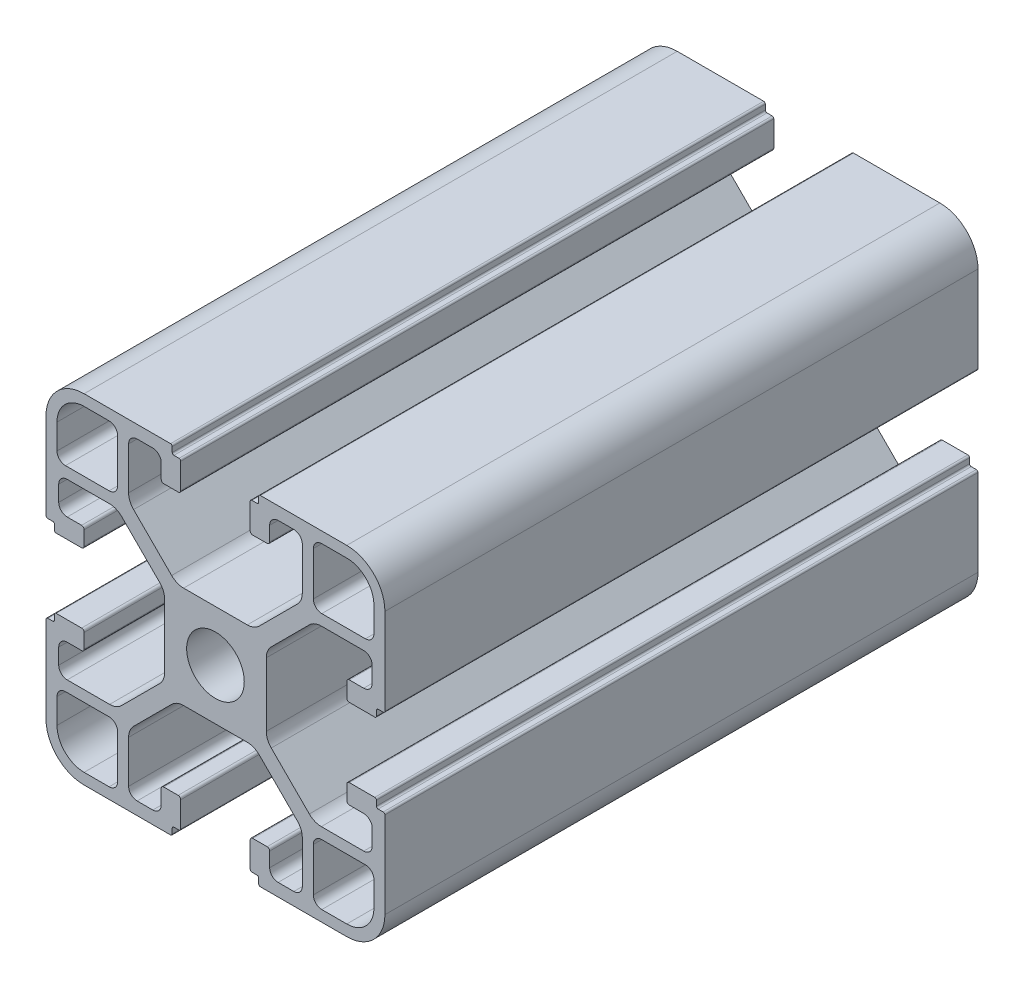
SolidWorks part; units mm, degrees
material "6063-T5"
ref_plane "Front Plane" through (0, 0, 0) normal (0, 0, 1) x (1, 0, 0)
ref_plane "Top Plane" through (0, 0, 0) normal (0, 1, 0) x (1, 0, 0)
ref_plane "Right Plane" through (0, 0, 0) normal (1, 0, 0) x (0, 0, -1)
sketch "Sketch2" plane through (0, 0, 0) normal (0, 0, 1) x (1, 0, 0)
  line L0 (4.5, 0) -> (14.7, 0)
  line L1 (40, 4.5) -> (40, 14.7)
  line L2 (35.5, 40) -> (25.3, 40)
  line L3 (0, 35.5) -> (0, 25.3)
  line L4 (15.9, 1.2) -> (15.9, 4.2)
  line L5 (24.1, 1.2) -> (24.1, 4.2)
  line L6 (38.8, 24.1) -> (35.8, 24.1)
  line L7 (35.5, 24.4) -> (35.5, 26.1)
  line L8 (14, 23.7574) -> (14, 16.2426)
  line L9 (16.2426, 14) -> (23.7574, 14)
  line L10 (26, 16.2426) -> (26, 23.7574)
  line L11 (13.4142, 14.8284) -> (8.9216, 10.3358)
  line L12 (23.7574, 26) -> (16.2426, 26)
  line L13 (4.5, 24.4) -> (4.5, 26.1)
  line L14 (1.2, 24.1) -> (4.2, 24.1)
  line L15 (15.9, 38.8) -> (15.9, 35.8)
  line L16 (14.8284, 26.5858) -> (10.3358, 31.0784)
  line L17 (13.4142, 25.1716) -> (8.9216, 29.6642)
  line L18 (14.8284, 13.4142) -> (10.3358, 8.9216)
  line L19 (25.1716, 13.4142) -> (29.6642, 8.9216)
  line L20 (26.5858, 14.8284) -> (31.0784, 10.3358)
  line L21 (26.5858, 25.1716) -> (31.0784, 29.6642)
  line L22 (25.1716, 26.5858) -> (29.6642, 31.0784)
  line L23 (24.1, 38.8) -> (24.1, 35.8)
  line L24 (14.7, 40) -> (4.5, 40)
  line L25 (25.3, 0) -> (35.5, 0)
  line L26 (38.8, 15.9) -> (35.8, 15.9)
  line L27 (40, 25.3) -> (40, 35.5)
  line L28 (1.2, 15.9) -> (4.2, 15.9)
  line L29 (0, 14.7) -> (0, 4.5)
  line L30 (4.5, 15.6) -> (4.5, 13.9)
  line L31 (35.5, 15.6) -> (35.5, 13.9)
  line L32 (15.6, 35.5) -> (13.9, 35.5)
  line L33 (24.4, 35.5) -> (26.1, 35.5)
  line L34 (15.6, 4.5) -> (13.9, 4.5)
  line L35 (24.4, 4.5) -> (26.1, 4.5)
  line L36 (12.6, 38.5) -> (10.75, 38.5)
  line L37 (1.5, 12.6) -> (1.5, 10.75)
  line L38 (27.4, 1.5) -> (29.25, 1.5)
  line L39 (38.5, 27.4) -> (38.5, 29.25)
  line L40 (38.5, 10.75) -> (38.5, 12.6)
  line L41 (29.25, 38.5) -> (27.4, 38.5)
  line L42 (1.5, 29.25) -> (1.5, 27.4)
  line L43 (10.75, 1.5) -> (12.6, 1.5)
  line L44 (35.8, 26.4) -> (37.5, 26.4)
  line L45 (35.8, 13.6) -> (37.5, 13.6)
  line L46 (4.2, 26.4) -> (2.5, 26.4)
  line L47 (13.6, 35.8) -> (13.6, 37.5)
  line L48 (26.4, 35.8) -> (26.4, 37.5)
  line L49 (4.2, 13.6) -> (2.5, 13.6)
  line L50 (13.6, 4.2) -> (13.6, 2.5)
  line L51 (26.4, 4.2) -> (26.4, 2.5)
  line L52 (9.75, 7.5074) -> (9.75, 2.5)
  line L53 (30.25, 7.5074) -> (30.25, 2.5)
  line L54 (9.75, 37.5) -> (9.75, 32.4926)
  line L55 (30.25, 37.5) -> (30.25, 32.4926)
  line L56 (32.4926, 30.25) -> (37.5, 30.25)
  line L57 (37.5, 9.75) -> (32.4926, 9.75)
  line L58 (2.5, 30.25) -> (7.5074, 30.25)
  line L59 (2.5, 9.75) -> (7.5074, 9.75)
  line L60 (31.55, 37.7) -> (31.55, 32.55)
  line L61 (32.55, 31.55) -> (37.7, 31.55)
  line L62 (1.3, 35.5) -> (1.3, 32.55)
  line L63 (4.5, 38.7) -> (7.45, 38.7)
  line L64 (32.55, 38.7) -> (35.5, 38.7)
  line L65 (38.7, 35.5) -> (38.7, 32.55)
  line L66 (8.45, 37.7) -> (8.45, 32.55)
  line L67 (2.3, 31.55) -> (7.45, 31.55)
  line L68 (1.3, 7.45) -> (1.3, 4.5)
  line L69 (2.3, 8.45) -> (7.45, 8.45)
  line L70 (8.45, 7.45) -> (8.45, 2.3)
  line L71 (4.5, 1.3) -> (7.45, 1.3)
  line L72 (31.55, 7.45) -> (31.55, 2.3)
  line L73 (32.55, 8.45) -> (37.7, 8.45)
  line L74 (38.7, 7.45) -> (38.7, 4.5)
  line L75 (32.55, 1.3) -> (35.5, 1.3)
  line L77 (14.9, 39.8) -> (14.9, 39.2)
  line L78 (15.1, 39) -> (15.7, 39)
  line L79 (25.1, 39.8) -> (25.1, 39.2)
  line L80 (24.9, 39) -> (24.3, 39)
  line L81 (25.1, 0.2) -> (25.1, 0.8)
  line L82 (24.9, 1) -> (24.3, 1)
  line L83 (14.9, 0.2) -> (14.9, 0.8)
  line L84 (15.1, 1) -> (15.7, 1)
  line L85 (0.2, 25.1) -> (0.8, 25.1)
  line L86 (1, 24.9) -> (1, 24.3)
  line L87 (0.2, 14.9) -> (0.8, 14.9)
  line L88 (1, 15.1) -> (1, 15.7)
  line L89 (39.8, 25.1) -> (39.2, 25.1)
  line L90 (39, 24.9) -> (39, 24.3)
  line L91 (39, 15.7) -> (39, 15.1)
  line L92 (39.2, 14.9) -> (39.8, 14.9)
  circle A0 centre (20, 20) radius 3.4
  arc A1 (1.3, 35.5) -> (4.5, 38.7) centre (4.5, 35.5) cw
  arc A2 (1.3, 4.5) -> (4.5, 1.3) centre (4.5, 4.5) ccw
  arc A3 (38.7, 4.5) -> (35.5, 1.3) centre (35.5, 4.5) cw
  arc A4 (35.5, 38.7) -> (38.7, 35.5) centre (35.5, 35.5) cw
  arc A5 (40, 35.5) -> (35.5, 40) centre (35.5, 35.5) ccw
  arc A6 (35.5, 0) -> (40, 4.5) centre (35.5, 4.5) ccw
  arc A7 (4.5, 0) -> (0, 4.5) centre (4.5, 4.5) cw
  arc A8 (4.5, 40) -> (0, 35.5) centre (4.5, 35.5) ccw
  arc A9 (13.4142, 14.8284) -> (14, 16.2426) centre (12, 16.2426) ccw
  arc A10 (7.5074, 9.75) -> (8.9216, 10.3358) centre (7.5074, 11.75) ccw
  arc A11 (9.75, 7.5074) -> (10.3358, 8.9216) centre (11.75, 7.5074) cw
  arc A12 (30.25, 7.5074) -> (29.6642, 8.9216) centre (28.25, 7.5074) ccw
  arc A13 (14.8284, 13.4142) -> (16.2426, 14) centre (16.2426, 12) cw
  arc A14 (25.1716, 13.4142) -> (23.7574, 14) centre (23.7574, 12) ccw
  arc A15 (32.4926, 9.75) -> (31.0784, 10.3358) centre (32.4926, 11.75) cw
  arc A16 (26.5858, 14.8284) -> (26, 16.2426) centre (28, 16.2426) cw
  arc A17 (32.4926, 30.25) -> (31.0784, 29.6642) centre (32.4926, 28.25) ccw
  arc A18 (26.5858, 25.1716) -> (26, 23.7574) centre (28, 23.7574) ccw
  arc A19 (13.4142, 25.1716) -> (14, 23.7574) centre (12, 23.7574) cw
  arc A20 (7.5074, 30.25) -> (8.9216, 29.6642) centre (7.5074, 28.25) cw
  arc A21 (9.75, 32.4926) -> (10.3358, 31.0784) centre (11.75, 32.4926) ccw
  arc A22 (30.25, 32.4926) -> (29.6642, 31.0784) centre (28.25, 32.4926) cw
  arc A23 (25.1716, 26.5858) -> (23.7574, 26) centre (23.7574, 28) cw
  arc A24 (14.8284, 26.5858) -> (16.2426, 26) centre (16.2426, 28) ccw
  arc A25 (37.7, 8.45) -> (38.7, 7.45) centre (37.7, 7.45) cw
  arc A26 (31.55, 2.3) -> (32.55, 1.3) centre (32.55, 2.3) ccw
  arc A27 (31.55, 7.45) -> (32.55, 8.45) centre (32.55, 7.45) cw
  arc A28 (8.45, 2.3) -> (7.45, 1.3) centre (7.45, 2.3) cw
  arc A29 (1.3, 7.45) -> (2.3, 8.45) centre (2.3, 7.45) cw
  arc A30 (7.45, 8.45) -> (8.45, 7.45) centre (7.45, 7.45) cw
  arc A31 (38.7, 32.55) -> (37.7, 31.55) centre (37.7, 32.55) cw
  arc A32 (31.55, 32.55) -> (32.55, 31.55) centre (32.55, 32.55) ccw
  arc A33 (31.55, 37.7) -> (32.55, 38.7) centre (32.55, 37.7) cw
  arc A34 (7.45, 38.7) -> (8.45, 37.7) centre (7.45, 37.7) cw
  arc A35 (8.45, 32.55) -> (7.45, 31.55) centre (7.45, 32.55) cw
  arc A36 (1.3, 32.55) -> (2.3, 31.55) centre (2.3, 32.55) ccw
  arc A37 (30.25, 2.5) -> (29.25, 1.5) centre (29.25, 2.5) cw
  arc A38 (26.4, 2.5) -> (27.4, 1.5) centre (27.4, 2.5) ccw
  arc A39 (13.6, 2.5) -> (12.6, 1.5) centre (12.6, 2.5) cw
  arc A40 (9.75, 2.5) -> (10.75, 1.5) centre (10.75, 2.5) ccw
  arc A41 (26.4, 37.5) -> (27.4, 38.5) centre (27.4, 37.5) cw
  arc A42 (30.25, 37.5) -> (29.25, 38.5) centre (29.25, 37.5) ccw
  arc A43 (37.5, 26.4) -> (38.5, 27.4) centre (37.5, 27.4) ccw
  arc A44 (37.5, 30.25) -> (38.5, 29.25) centre (37.5, 29.25) cw
  arc A45 (37.5, 13.6) -> (38.5, 12.6) centre (37.5, 12.6) cw
  arc A46 (37.5, 9.75) -> (38.5, 10.75) centre (37.5, 10.75) ccw
  arc A47 (2.5, 9.75) -> (1.5, 10.75) centre (2.5, 10.75) cw
  arc A48 (2.5, 13.6) -> (1.5, 12.6) centre (2.5, 12.6) ccw
  arc A49 (2.5, 26.4) -> (1.5, 27.4) centre (2.5, 27.4) cw
  arc A50 (2.5, 30.25) -> (1.5, 29.25) centre (2.5, 29.25) ccw
  arc A51 (9.75, 37.5) -> (10.75, 38.5) centre (10.75, 37.5) cw
  arc A52 (13.6, 37.5) -> (12.6, 38.5) centre (12.6, 37.5) ccw
  arc A53 (26.1, 35.5) -> (26.4, 35.8) centre (26.1, 35.8) ccw
  arc A54 (24.1, 35.8) -> (24.4, 35.5) centre (24.4, 35.8) ccw
  arc A55 (15.9, 35.8) -> (15.6, 35.5) centre (15.6, 35.8) cw
  arc A56 (13.9, 35.5) -> (13.6, 35.8) centre (13.9, 35.8) cw
  arc A57 (13.9, 4.5) -> (13.6, 4.2) centre (13.9, 4.2) ccw
  arc A58 (15.9, 4.2) -> (15.6, 4.5) centre (15.6, 4.2) ccw
  arc A59 (24.1, 4.2) -> (24.4, 4.5) centre (24.4, 4.2) cw
  arc A60 (26.1, 4.5) -> (26.4, 4.2) centre (26.1, 4.2) cw
  arc A61 (35.5, 13.9) -> (35.8, 13.6) centre (35.8, 13.9) ccw
  arc A62 (35.8, 15.9) -> (35.5, 15.6) centre (35.8, 15.6) ccw
  arc A63 (35.8, 24.1) -> (35.5, 24.4) centre (35.8, 24.4) cw
  arc A64 (35.5, 26.1) -> (35.8, 26.4) centre (35.8, 26.1) cw
  arc A65 (4.5, 13.9) -> (4.2, 13.6) centre (4.2, 13.9) cw
  arc A66 (4.2, 15.9) -> (4.5, 15.6) centre (4.2, 15.6) cw
  arc A67 (4.2, 24.1) -> (4.5, 24.4) centre (4.2, 24.4) ccw
  arc A68 (4.5, 26.1) -> (4.2, 26.4) centre (4.2, 26.1) ccw
  arc A69 (25.3, 0) -> (25.1, 0.2) centre (25.3, 0.2) cw
  arc A70 (25.1, 0.8) -> (24.9, 1) centre (24.9, 0.8) ccw
  arc A71 (24.3, 1) -> (24.1, 1.2) centre (24.3, 1.2) cw
  arc A72 (14.7, 0) -> (14.9, 0.2) centre (14.7, 0.2) ccw
  arc A73 (14.9, 0.8) -> (15.1, 1) centre (15.1, 0.8) cw
  arc A74 (15.7, 1) -> (15.9, 1.2) centre (15.7, 1.2) ccw
  arc A75 (39.8, 14.9) -> (40, 14.7) centre (39.8, 14.7) cw
  arc A76 (39, 15.1) -> (39.2, 14.9) centre (39.2, 15.1) ccw
  arc A77 (38.8, 15.9) -> (39, 15.7) centre (38.8, 15.7) cw
  arc A78 (0, 25.3) -> (0.2, 25.1) centre (0.2, 25.3) ccw
  arc A79 (0.8, 25.1) -> (1, 24.9) centre (0.8, 24.9) cw
  arc A80 (1, 24.3) -> (1.2, 24.1) centre (1.2, 24.3) ccw
  arc A81 (0, 14.7) -> (0.2, 14.9) centre (0.2, 14.7) cw
  arc A82 (0.8, 14.9) -> (1, 15.1) centre (0.8, 15.1) ccw
  arc A83 (1, 15.7) -> (1.2, 15.9) centre (1.2, 15.7) cw
  arc A84 (39, 24.3) -> (38.8, 24.1) centre (38.8, 24.3) cw
  arc A85 (39.2, 25.1) -> (39, 24.9) centre (39.2, 24.9) ccw
  arc A86 (40, 25.3) -> (39.8, 25.1) centre (39.8, 25.3) cw
  arc A87 (24.3, 39) -> (24.1, 38.8) centre (24.3, 38.8) ccw
  arc A88 (25.1, 39.2) -> (24.9, 39) centre (24.9, 39.2) cw
  arc A89 (25.3, 40) -> (25.1, 39.8) centre (25.3, 39.8) ccw
  arc A90 (14.9, 39.2) -> (15.1, 39) centre (15.1, 39.2) ccw
  arc A91 (15.7, 39) -> (15.9, 38.8) centre (15.7, 38.8) cw
  arc A92 (14.7, 40) -> (14.9, 39.8) centre (14.7, 39.8) cw
  point P93 (0, 0)
extrude "Boss-Extrude1" add sketch "Sketch2" along normal blind 70
sketch "Sketch3" plane through (0, 0, 70) normal (0, 0, 1) x (1, 0, 0)
  line L76 (25.3, 0) -> (35.5, 0)
  line L77 (40, 4.5) -> (40, 14.7)
  line L78 (39.8, 14.9) -> (39.2, 14.9)
  line L79 (39, 15.1) -> (39, 15.7)
  line L80 (38.8, 15.9) -> (35.8, 15.9)
  line L81 (35.5, 15.6) -> (35.5, 13.9)
  line L82 (35.8, 13.6) -> (37.5, 13.6)
  line L83 (38.5, 12.6) -> (38.5, 10.75)
  line L84 (37.5, 9.75) -> (32.4926, 9.75)
  line L85 (31.0784, 10.3358) -> (26.5858, 14.8284)
  line L86 (26, 16.2426) -> (26, 23.7574)
  line L87 (26.5858, 25.1716) -> (31.0784, 29.6642)
  line L88 (32.4926, 30.25) -> (37.5, 30.25)
  line L89 (38.5, 29.25) -> (38.5, 27.4)
  line L90 (37.5, 26.4) -> (35.8, 26.4)
  line L91 (35.5, 26.1) -> (35.5, 24.4)
  line L92 (35.8, 24.1) -> (38.8, 24.1)
  line L93 (39, 24.3) -> (39, 24.9)
  line L94 (39.2, 25.1) -> (39.8, 25.1)
  line L95 (40, 25.3) -> (40, 35.5)
  line L96 (35.5, 40) -> (25.3, 40)
  line L97 (25.1, 39.8) -> (25.1, 39.2)
  line L98 (24.9, 39) -> (24.3, 39)
  line L99 (24.1, 38.8) -> (24.1, 35.8)
  line L100 (24.4, 35.5) -> (26.1, 35.5)
  line L101 (26.4, 35.8) -> (26.4, 37.5)
  line L102 (27.4, 38.5) -> (29.25, 38.5)
  line L103 (30.25, 37.5) -> (30.25, 32.4926)
  line L104 (29.6642, 31.0784) -> (25.1716, 26.5858)
  line L105 (23.7574, 26) -> (16.2426, 26)
  line L106 (14.8284, 26.5858) -> (10.3358, 31.0784)
  line L107 (9.75, 32.4926) -> (9.75, 37.5)
  line L108 (10.75, 38.5) -> (12.6, 38.5)
  line L109 (13.6, 37.5) -> (13.6, 35.8)
  line L110 (13.9, 35.5) -> (15.6, 35.5)
  line L111 (15.9, 35.8) -> (15.9, 38.8)
  line L112 (15.7, 39) -> (15.1, 39)
  line L113 (14.9, 39.2) -> (14.9, 39.8)
  line L114 (14.7, 40) -> (4.5, 40)
  line L115 (0, 35.5) -> (0, 25.3)
  line L116 (0.2, 25.1) -> (0.8, 25.1)
  line L117 (1, 24.9) -> (1, 24.3)
  line L118 (1.2, 24.1) -> (4.2, 24.1)
  line L119 (4.5, 24.4) -> (4.5, 26.1)
  line L120 (4.2, 26.4) -> (2.5, 26.4)
  line L121 (1.5, 27.4) -> (1.5, 29.25)
  line L122 (2.5, 30.25) -> (7.5074, 30.25)
  line L123 (8.9216, 29.6642) -> (13.4142, 25.1716)
  line L124 (14, 23.7574) -> (14, 16.2426)
  line L125 (13.4142, 14.8284) -> (8.9216, 10.3358)
  line L126 (7.5074, 9.75) -> (2.5, 9.75)
  line L127 (1.5, 10.75) -> (1.5, 12.6)
  line L128 (2.5, 13.6) -> (4.2, 13.6)
  line L129 (4.5, 13.9) -> (4.5, 15.6)
  line L130 (4.2, 15.9) -> (1.2, 15.9)
  line L131 (1, 15.7) -> (1, 15.1)
  line L132 (0.8, 14.9) -> (0.2, 14.9)
  line L133 (0, 14.7) -> (0, 4.5)
  line L134 (4.5, 0) -> (14.7, 0)
  line L135 (14.9, 0.2) -> (14.9, 0.8)
  line L136 (15.1, 1) -> (15.7, 1)
  line L137 (15.9, 1.2) -> (15.9, 4.2)
  line L138 (15.6, 4.5) -> (13.9, 4.5)
  line L139 (13.6, 4.2) -> (13.6, 2.5)
  line L140 (12.6, 1.5) -> (10.75, 1.5)
  line L141 (9.75, 2.5) -> (9.75, 7.5074)
  line L142 (10.3358, 8.9216) -> (14.8284, 13.4142)
  line L143 (16.2426, 14) -> (23.7574, 14)
  line L144 (25.1716, 13.4142) -> (29.6642, 8.9216)
  line L145 (30.25, 7.5074) -> (30.25, 2.5)
  line L146 (29.25, 1.5) -> (27.4, 1.5)
  line L147 (26.4, 2.5) -> (26.4, 4.2)
  line L148 (26.1, 4.5) -> (24.4, 4.5)
  line L149 (24.1, 4.2) -> (24.1, 1.2)
  line L150 (24.3, 1) -> (24.9, 1)
  line L151 (25.1, 0.8) -> (25.1, 0.2)
  line L152 (25.3, 0) -> (35.5, 0)
  line L153 (40, 4.5) -> (40, 14.7)
  line L154 (39.8, 14.9) -> (39.2, 14.9)
  line L155 (39, 15.1) -> (39, 15.7)
  line L156 (38.8, 15.9) -> (35.8, 15.9)
  line L157 (35.5, 15.6) -> (35.5, 13.9)
  line L158 (35.8, 13.6) -> (37.5, 13.6)
  line L159 (38.5, 12.6) -> (38.5, 10.75)
  line L160 (37.5, 9.75) -> (32.4926, 9.75)
  line L161 (31.0784, 10.3358) -> (26.5858, 14.8284)
  line L162 (26, 16.2426) -> (26, 23.7574)
  line L163 (26.5858, 25.1716) -> (31.0784, 29.6642)
  line L164 (32.4926, 30.25) -> (37.5, 30.25)
  line L165 (38.5, 29.25) -> (38.5, 27.4)
  line L166 (37.5, 26.4) -> (35.8, 26.4)
  line L167 (35.5, 26.1) -> (35.5, 24.4)
  line L168 (35.8, 24.1) -> (38.8, 24.1)
  line L169 (39, 24.3) -> (39, 24.9)
  line L170 (39.2, 25.1) -> (39.8, 25.1)
  line L171 (40, 25.3) -> (40, 35.5)
  line L172 (35.5, 40) -> (25.3, 40)
  line L173 (25.1, 39.8) -> (25.1, 39.2)
  line L174 (24.9, 39) -> (24.3, 39)
  line L175 (24.1, 38.8) -> (24.1, 35.8)
  line L176 (24.4, 35.5) -> (26.1, 35.5)
  line L177 (26.4, 35.8) -> (26.4, 37.5)
  line L178 (27.4, 38.5) -> (29.25, 38.5)
  line L179 (30.25, 37.5) -> (30.25, 32.4926)
  line L180 (29.6642, 31.0784) -> (25.1716, 26.5858)
  line L181 (23.7574, 26) -> (16.2426, 26)
  line L182 (14.8284, 26.5858) -> (10.3358, 31.0784)
  line L183 (9.75, 32.4926) -> (9.75, 37.5)
  line L184 (10.75, 38.5) -> (12.6, 38.5)
  line L185 (13.6, 37.5) -> (13.6, 35.8)
  line L186 (13.9, 35.5) -> (15.6, 35.5)
  line L187 (15.9, 35.8) -> (15.9, 38.8)
  line L188 (15.7, 39) -> (15.1, 39)
  line L189 (14.9, 39.2) -> (14.9, 39.8)
  line L190 (14.7, 40) -> (4.5, 40)
  line L191 (0, 35.5) -> (0, 25.3)
  line L192 (0.2, 25.1) -> (0.8, 25.1)
  line L193 (1, 24.9) -> (1, 24.3)
  line L194 (1.2, 24.1) -> (4.2, 24.1)
  line L195 (4.5, 24.4) -> (4.5, 26.1)
  line L196 (4.2, 26.4) -> (2.5, 26.4)
  line L197 (1.5, 27.4) -> (1.5, 29.25)
  line L198 (2.5, 30.25) -> (7.5074, 30.25)
  line L199 (8.9216, 29.6642) -> (13.4142, 25.1716)
  line L200 (14, 23.7574) -> (14, 16.2426)
  line L201 (13.4142, 14.8284) -> (8.9216, 10.3358)
  line L202 (7.5074, 9.75) -> (2.5, 9.75)
  line L203 (1.5, 10.75) -> (1.5, 12.6)
  line L204 (2.5, 13.6) -> (4.2, 13.6)
  line L205 (4.5, 13.9) -> (4.5, 15.6)
  line L206 (4.2, 15.9) -> (1.2, 15.9)
  line L207 (1, 15.7) -> (1, 15.1)
  line L208 (0.8, 14.9) -> (0.2, 14.9)
  line L209 (0, 14.7) -> (0, 4.5)
  line L210 (4.5, 0) -> (14.7, 0)
  line L211 (14.9, 0.2) -> (14.9, 0.8)
  line L212 (15.1, 1) -> (15.7, 1)
  line L213 (15.9, 1.2) -> (15.9, 4.2)
  line L214 (15.6, 4.5) -> (13.9, 4.5)
  line L215 (13.6, 4.2) -> (13.6, 2.5)
  line L216 (12.6, 1.5) -> (10.75, 1.5)
  line L217 (9.75, 2.5) -> (9.75, 7.5074)
  line L218 (10.3358, 8.9216) -> (14.8284, 13.4142)
  line L219 (16.2426, 14) -> (23.7574, 14)
  line L220 (25.1716, 13.4142) -> (29.6642, 8.9216)
  line L221 (30.25, 7.5074) -> (30.25, 2.5)
  line L222 (29.25, 1.5) -> (27.4, 1.5)
  line L223 (26.4, 2.5) -> (26.4, 4.2)
  line L224 (26.1, 4.5) -> (24.4, 4.5)
  line L225 (24.1, 4.2) -> (24.1, 1.2)
  line L226 (24.3, 1) -> (24.9, 1)
  line L227 (25.1, 0.8) -> (25.1, 0.2)
  arc A76 (25.1, 0.2) -> (25.3, 0) centre (25.3, 0.2) ccw
  arc A77 (35.5, 0) -> (40, 4.5) centre (35.5, 4.5) ccw
  arc A78 (40, 14.7) -> (39.8, 14.9) centre (39.8, 14.7) ccw
  arc A79 (39, 15.1) -> (39.2, 14.9) centre (39.2, 15.1) ccw
  arc A80 (39, 15.7) -> (38.8, 15.9) centre (38.8, 15.7) ccw
  arc A81 (35.8, 15.9) -> (35.5, 15.6) centre (35.8, 15.6) ccw
  arc A82 (35.5, 13.9) -> (35.8, 13.6) centre (35.8, 13.9) ccw
  arc A83 (38.5, 12.6) -> (37.5, 13.6) centre (37.5, 12.6) ccw
  arc A84 (37.5, 9.75) -> (38.5, 10.75) centre (37.5, 10.75) ccw
  arc A85 (31.0784, 10.3358) -> (32.4926, 9.75) centre (32.4926, 11.75) ccw
  arc A86 (26, 16.2426) -> (26.5858, 14.8284) centre (28, 16.2426) ccw
  arc A87 (26.5858, 25.1716) -> (26, 23.7574) centre (28, 23.7574) ccw
  arc A88 (32.4926, 30.25) -> (31.0784, 29.6642) centre (32.4926, 28.25) ccw
  arc A89 (38.5, 29.25) -> (37.5, 30.25) centre (37.5, 29.25) ccw
  arc A90 (37.5, 26.4) -> (38.5, 27.4) centre (37.5, 27.4) ccw
  arc A91 (35.8, 26.4) -> (35.5, 26.1) centre (35.8, 26.1) ccw
  arc A92 (35.5, 24.4) -> (35.8, 24.1) centre (35.8, 24.4) ccw
  arc A93 (38.8, 24.1) -> (39, 24.3) centre (38.8, 24.3) ccw
  arc A94 (39.2, 25.1) -> (39, 24.9) centre (39.2, 24.9) ccw
  arc A95 (39.8, 25.1) -> (40, 25.3) centre (39.8, 25.3) ccw
  arc A96 (40, 35.5) -> (35.5, 40) centre (35.5, 35.5) ccw
  arc A97 (25.3, 40) -> (25.1, 39.8) centre (25.3, 39.8) ccw
  arc A98 (24.9, 39) -> (25.1, 39.2) centre (24.9, 39.2) ccw
  arc A99 (24.3, 39) -> (24.1, 38.8) centre (24.3, 38.8) ccw
  arc A100 (24.1, 35.8) -> (24.4, 35.5) centre (24.4, 35.8) ccw
  arc A101 (26.1, 35.5) -> (26.4, 35.8) centre (26.1, 35.8) ccw
  arc A102 (27.4, 38.5) -> (26.4, 37.5) centre (27.4, 37.5) ccw
  arc A103 (30.25, 37.5) -> (29.25, 38.5) centre (29.25, 37.5) ccw
  arc A104 (29.6642, 31.0784) -> (30.25, 32.4926) centre (28.25, 32.4926) ccw
  arc A105 (23.7574, 26) -> (25.1716, 26.5858) centre (23.7574, 28) ccw
  arc A106 (14.8284, 26.5858) -> (16.2426, 26) centre (16.2426, 28) ccw
  arc A107 (9.75, 32.4926) -> (10.3358, 31.0784) centre (11.75, 32.4926) ccw
  arc A108 (10.75, 38.5) -> (9.75, 37.5) centre (10.75, 37.5) ccw
  arc A109 (13.6, 37.5) -> (12.6, 38.5) centre (12.6, 37.5) ccw
  arc A110 (13.6, 35.8) -> (13.9, 35.5) centre (13.9, 35.8) ccw
  arc A111 (15.6, 35.5) -> (15.9, 35.8) centre (15.6, 35.8) ccw
  arc A112 (15.9, 38.8) -> (15.7, 39) centre (15.7, 38.8) ccw
  arc A113 (14.9, 39.2) -> (15.1, 39) centre (15.1, 39.2) ccw
  arc A114 (14.9, 39.8) -> (14.7, 40) centre (14.7, 39.8) ccw
  arc A115 (4.5, 40) -> (0, 35.5) centre (4.5, 35.5) ccw
  arc A116 (0, 25.3) -> (0.2, 25.1) centre (0.2, 25.3) ccw
  arc A117 (1, 24.9) -> (0.8, 25.1) centre (0.8, 24.9) ccw
  arc A118 (1, 24.3) -> (1.2, 24.1) centre (1.2, 24.3) ccw
  arc A119 (4.2, 24.1) -> (4.5, 24.4) centre (4.2, 24.4) ccw
  arc A120 (4.5, 26.1) -> (4.2, 26.4) centre (4.2, 26.1) ccw
  arc A121 (1.5, 27.4) -> (2.5, 26.4) centre (2.5, 27.4) ccw
  arc A122 (2.5, 30.25) -> (1.5, 29.25) centre (2.5, 29.25) ccw
  arc A123 (8.9216, 29.6642) -> (7.5074, 30.25) centre (7.5074, 28.25) ccw
  arc A124 (14, 23.7574) -> (13.4142, 25.1716) centre (12, 23.7574) ccw
  arc A125 (13.4142, 14.8284) -> (14, 16.2426) centre (12, 16.2426) ccw
  arc A126 (7.5074, 9.75) -> (8.9216, 10.3358) centre (7.5074, 11.75) ccw
  arc A127 (1.5, 10.75) -> (2.5, 9.75) centre (2.5, 10.75) ccw
  arc A128 (2.5, 13.6) -> (1.5, 12.6) centre (2.5, 12.6) ccw
  arc A129 (4.2, 13.6) -> (4.5, 13.9) centre (4.2, 13.9) ccw
  arc A130 (4.5, 15.6) -> (4.2, 15.9) centre (4.2, 15.6) ccw
  arc A131 (1.2, 15.9) -> (1, 15.7) centre (1.2, 15.7) ccw
  arc A132 (0.8, 14.9) -> (1, 15.1) centre (0.8, 15.1) ccw
  arc A133 (0.2, 14.9) -> (0, 14.7) centre (0.2, 14.7) ccw
  arc A134 (0, 4.5) -> (4.5, 0) centre (4.5, 4.5) ccw
  arc A135 (14.7, 0) -> (14.9, 0.2) centre (14.7, 0.2) ccw
  arc A136 (15.1, 1) -> (14.9, 0.8) centre (15.1, 0.8) ccw
  arc A137 (15.7, 1) -> (15.9, 1.2) centre (15.7, 1.2) ccw
  arc A138 (15.9, 4.2) -> (15.6, 4.5) centre (15.6, 4.2) ccw
  arc A139 (13.9, 4.5) -> (13.6, 4.2) centre (13.9, 4.2) ccw
  arc A140 (12.6, 1.5) -> (13.6, 2.5) centre (12.6, 2.5) ccw
  arc A141 (9.75, 2.5) -> (10.75, 1.5) centre (10.75, 2.5) ccw
  arc A142 (10.3358, 8.9216) -> (9.75, 7.5074) centre (11.75, 7.5074) ccw
  arc A143 (16.2426, 14) -> (14.8284, 13.4142) centre (16.2426, 12) ccw
  arc A144 (25.1716, 13.4142) -> (23.7574, 14) centre (23.7574, 12) ccw
  arc A145 (30.25, 7.5074) -> (29.6642, 8.9216) centre (28.25, 7.5074) ccw
  arc A146 (29.25, 1.5) -> (30.25, 2.5) centre (29.25, 2.5) ccw
  arc A147 (26.4, 2.5) -> (27.4, 1.5) centre (27.4, 2.5) ccw
  arc A148 (26.4, 4.2) -> (26.1, 4.5) centre (26.1, 4.2) ccw
  arc A149 (24.4, 4.5) -> (24.1, 4.2) centre (24.4, 4.2) ccw
  arc A150 (24.1, 1.2) -> (24.3, 1) centre (24.3, 1.2) ccw
  arc A151 (25.1, 0.8) -> (24.9, 1) centre (24.9, 0.8) ccw
  arc A152 (25.1, 0.2) -> (25.3, 0) centre (25.3, 0.2) ccw
  arc A153 (35.5, 0) -> (40, 4.5) centre (35.5, 4.5) ccw
  arc A154 (40, 14.7) -> (39.8, 14.9) centre (39.8, 14.7) ccw
  arc A155 (39, 15.1) -> (39.2, 14.9) centre (39.2, 15.1) ccw
  arc A156 (39, 15.7) -> (38.8, 15.9) centre (38.8, 15.7) ccw
  arc A157 (35.8, 15.9) -> (35.5, 15.6) centre (35.8, 15.6) ccw
  arc A158 (35.5, 13.9) -> (35.8, 13.6) centre (35.8, 13.9) ccw
  arc A159 (38.5, 12.6) -> (37.5, 13.6) centre (37.5, 12.6) ccw
  arc A160 (37.5, 9.75) -> (38.5, 10.75) centre (37.5, 10.75) ccw
  arc A161 (31.0784, 10.3358) -> (32.4926, 9.75) centre (32.4926, 11.75) ccw
  arc A162 (26, 16.2426) -> (26.5858, 14.8284) centre (28, 16.2426) ccw
  arc A163 (26.5858, 25.1716) -> (26, 23.7574) centre (28, 23.7574) ccw
  arc A164 (32.4926, 30.25) -> (31.0784, 29.6642) centre (32.4926, 28.25) ccw
  arc A165 (38.5, 29.25) -> (37.5, 30.25) centre (37.5, 29.25) ccw
  arc A166 (37.5, 26.4) -> (38.5, 27.4) centre (37.5, 27.4) ccw
  arc A167 (35.8, 26.4) -> (35.5, 26.1) centre (35.8, 26.1) ccw
  arc A168 (35.5, 24.4) -> (35.8, 24.1) centre (35.8, 24.4) ccw
  arc A169 (38.8, 24.1) -> (39, 24.3) centre (38.8, 24.3) ccw
  arc A170 (39.2, 25.1) -> (39, 24.9) centre (39.2, 24.9) ccw
  arc A171 (39.8, 25.1) -> (40, 25.3) centre (39.8, 25.3) ccw
  arc A172 (40, 35.5) -> (35.5, 40) centre (35.5, 35.5) ccw
  arc A173 (25.3, 40) -> (25.1, 39.8) centre (25.3, 39.8) ccw
  arc A174 (24.9, 39) -> (25.1, 39.2) centre (24.9, 39.2) ccw
  arc A175 (24.3, 39) -> (24.1, 38.8) centre (24.3, 38.8) ccw
  arc A176 (24.1, 35.8) -> (24.4, 35.5) centre (24.4, 35.8) ccw
  arc A177 (26.1, 35.5) -> (26.4, 35.8) centre (26.1, 35.8) ccw
  arc A178 (27.4, 38.5) -> (26.4, 37.5) centre (27.4, 37.5) ccw
  arc A179 (30.25, 37.5) -> (29.25, 38.5) centre (29.25, 37.5) ccw
  arc A180 (29.6642, 31.0784) -> (30.25, 32.4926) centre (28.25, 32.4926) ccw
  arc A181 (23.7574, 26) -> (25.1716, 26.5858) centre (23.7574, 28) ccw
  arc A182 (14.8284, 26.5858) -> (16.2426, 26) centre (16.2426, 28) ccw
  arc A183 (9.75, 32.4926) -> (10.3358, 31.0784) centre (11.75, 32.4926) ccw
  arc A184 (10.75, 38.5) -> (9.75, 37.5) centre (10.75, 37.5) ccw
  arc A185 (13.6, 37.5) -> (12.6, 38.5) centre (12.6, 37.5) ccw
  arc A186 (13.6, 35.8) -> (13.9, 35.5) centre (13.9, 35.8) ccw
  arc A187 (15.6, 35.5) -> (15.9, 35.8) centre (15.6, 35.8) ccw
  arc A188 (15.9, 38.8) -> (15.7, 39) centre (15.7, 38.8) ccw
  arc A189 (14.9, 39.2) -> (15.1, 39) centre (15.1, 39.2) ccw
  arc A190 (14.9, 39.8) -> (14.7, 40) centre (14.7, 39.8) ccw
  arc A191 (4.5, 40) -> (0, 35.5) centre (4.5, 35.5) ccw
  arc A192 (0, 25.3) -> (0.2, 25.1) centre (0.2, 25.3) ccw
  arc A193 (1, 24.9) -> (0.8, 25.1) centre (0.8, 24.9) ccw
  arc A194 (1, 24.3) -> (1.2, 24.1) centre (1.2, 24.3) ccw
  arc A195 (4.2, 24.1) -> (4.5, 24.4) centre (4.2, 24.4) ccw
  arc A196 (4.5, 26.1) -> (4.2, 26.4) centre (4.2, 26.1) ccw
  arc A197 (1.5, 27.4) -> (2.5, 26.4) centre (2.5, 27.4) ccw
  arc A198 (2.5, 30.25) -> (1.5, 29.25) centre (2.5, 29.25) ccw
  arc A199 (8.9216, 29.6642) -> (7.5074, 30.25) centre (7.5074, 28.25) ccw
  arc A200 (14, 23.7574) -> (13.4142, 25.1716) centre (12, 23.7574) ccw
  arc A201 (13.4142, 14.8284) -> (14, 16.2426) centre (12, 16.2426) ccw
  arc A202 (7.5074, 9.75) -> (8.9216, 10.3358) centre (7.5074, 11.75) ccw
  arc A203 (1.5, 10.75) -> (2.5, 9.75) centre (2.5, 10.75) ccw
  arc A204 (2.5, 13.6) -> (1.5, 12.6) centre (2.5, 12.6) ccw
  arc A205 (4.2, 13.6) -> (4.5, 13.9) centre (4.2, 13.9) ccw
  arc A206 (4.5, 15.6) -> (4.2, 15.9) centre (4.2, 15.6) ccw
  arc A207 (1.2, 15.9) -> (1, 15.7) centre (1.2, 15.7) ccw
  arc A208 (0.8, 14.9) -> (1, 15.1) centre (0.8, 15.1) ccw
  arc A209 (0.2, 14.9) -> (0, 14.7) centre (0.2, 14.7) ccw
  arc A210 (0, 4.5) -> (4.5, 0) centre (4.5, 4.5) ccw
  arc A211 (14.7, 0) -> (14.9, 0.2) centre (14.7, 0.2) ccw
  arc A212 (15.1, 1) -> (14.9, 0.8) centre (15.1, 0.8) ccw
  arc A213 (15.7, 1) -> (15.9, 1.2) centre (15.7, 1.2) ccw
  arc A214 (15.9, 4.2) -> (15.6, 4.5) centre (15.6, 4.2) ccw
  arc A215 (13.9, 4.5) -> (13.6, 4.2) centre (13.9, 4.2) ccw
  arc A216 (12.6, 1.5) -> (13.6, 2.5) centre (12.6, 2.5) ccw
  arc A217 (9.75, 2.5) -> (10.75, 1.5) centre (10.75, 2.5) ccw
  arc A218 (10.3358, 8.9216) -> (9.75, 7.5074) centre (11.75, 7.5074) ccw
  arc A219 (16.2426, 14) -> (14.8284, 13.4142) centre (16.2426, 12) ccw
  arc A220 (25.1716, 13.4142) -> (23.7574, 14) centre (23.7574, 12) ccw
  arc A221 (30.25, 7.5074) -> (29.6642, 8.9216) centre (28.25, 7.5074) ccw
  arc A222 (29.25, 1.5) -> (30.25, 2.5) centre (29.25, 2.5) ccw
  arc A223 (26.4, 2.5) -> (27.4, 1.5) centre (27.4, 2.5) ccw
  arc A224 (26.4, 4.2) -> (26.1, 4.5) centre (26.1, 4.2) ccw
  arc A225 (24.4, 4.5) -> (24.1, 4.2) centre (24.4, 4.2) ccw
  arc A226 (24.1, 1.2) -> (24.3, 1) centre (24.3, 1.2) ccw
  arc A227 (25.1, 0.8) -> (24.9, 1) centre (24.9, 0.8) ccw
  dimension "D1" = 0
